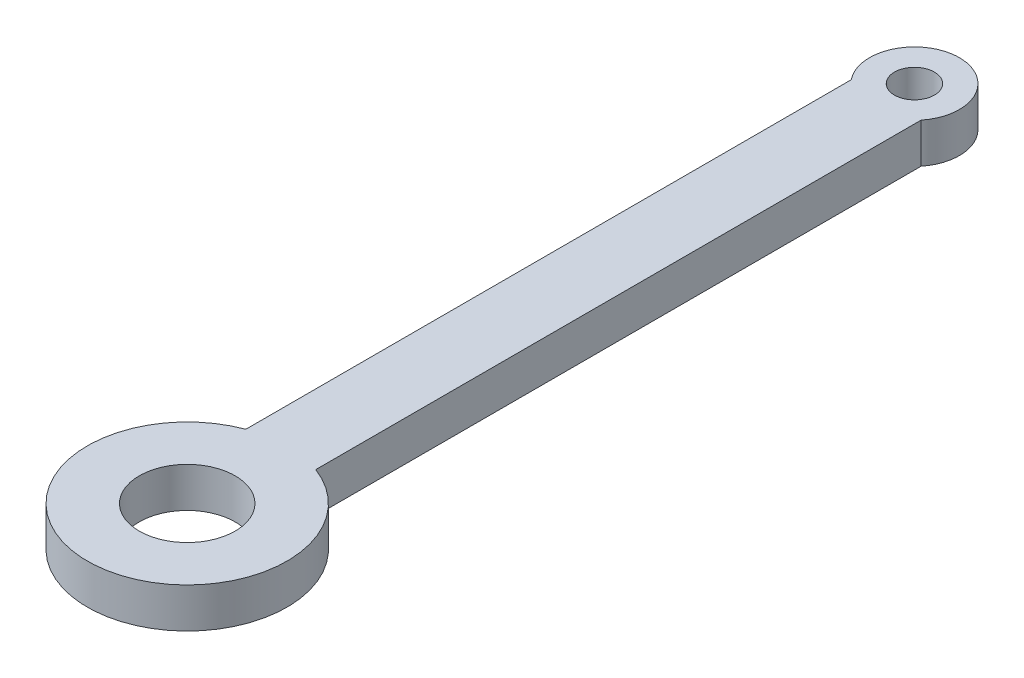
SolidWorks part; units mm, degrees
ref_plane "Front Plane" through (0, 0, 0) normal (0, 0, 1) x (1, 0, 0)
ref_plane "Top Plane" through (0, 0, 0) normal (0, 1, 0) x (1, 0, 0)
ref_plane "Right Plane" through (0, 0, 0) normal (1, 0, 0) x (0, 0, -1)
sketch "Sketch1" plane through (0, 0, 0) normal (0, 1, 0) x (1, 0, 0)
  line L1 (-1.7496, 4.6839) -> (-1.7496, 34.9953)
  line L2 (1.7504, 4.6836) -> (1.7504, 34.9963)
  circle A0 centre (0, 0) radius 2.4
  arc A1 (-1.7496, 4.6839) -> (1.7504, 4.6836) centre (0, 0) ccw
  circle A2 centre (0, 36.41) radius 1
  arc A3 (1.7504, 34.9963) -> (-1.7496, 34.9953) centre (0, 36.41) ccw
  point P8 (0, 0)
  point P9 (0, 0)
  point P10 (0, 0)
  point P14 (0, 0)
  point P15 (0, 0)
  point P16 (0, 0)
  point P17 (-1.75, 35.0543)
  point P18 (-1.75, 35.0763)
  point P19 (0, 0)
  point P20 (0, 0)
  point P21 (0, 0)
  dimension "D1" = 2
  dimension "D2" = 4.5
  dimension "D3" = 10
  dimension "D4" = 4.8
  dimension "D5" = 3.5
  dimension "D6" = 36.41
  dimension "D7" = 30.3114
extrude "Boss-Extrude1" add sketch "Sketch1" along normal blind 2
